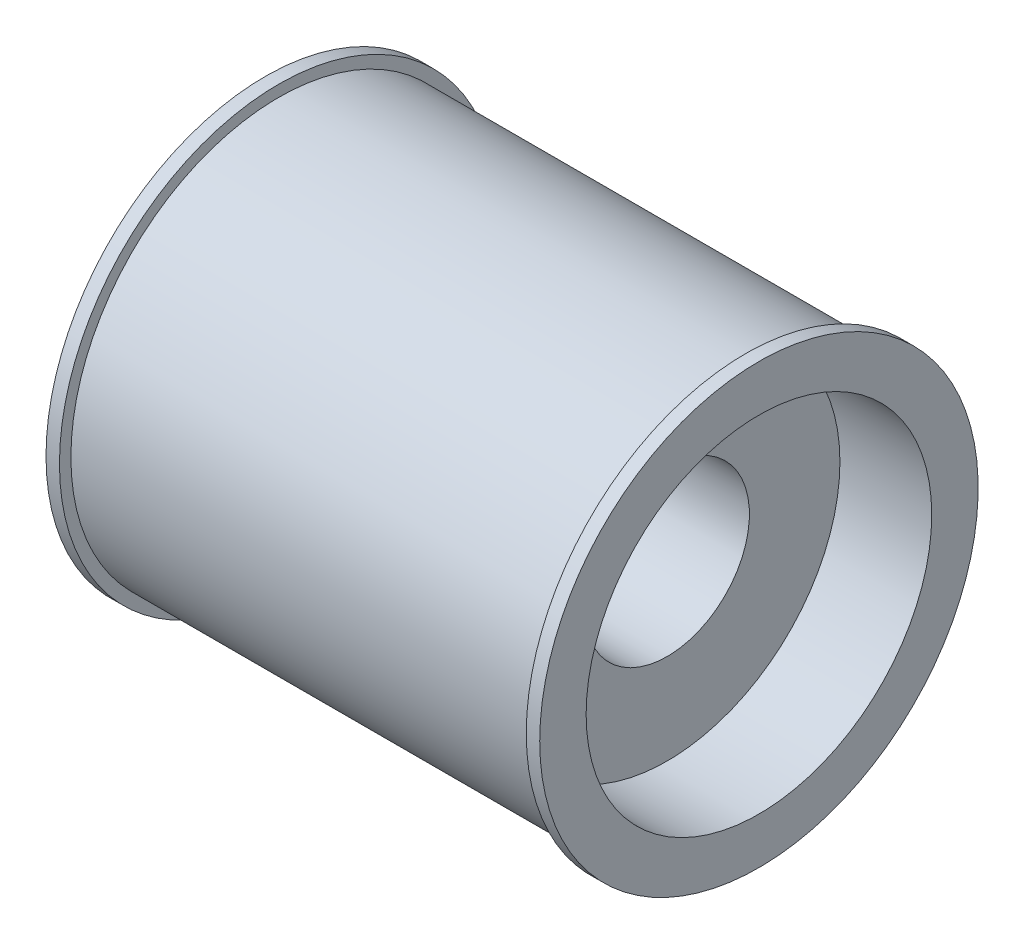
SolidWorks part; units mm, degrees
ref_plane "Front Plane" through (0, 0, 0) normal (0, 0, 1) x (1, 0, 0)
ref_plane "Top Plane" through (0, 0, 0) normal (0, 1, 0) x (1, 0, 0)
ref_plane "Right Plane" through (0, 0, 0) normal (1, 0, 0) x (0, 0, -1)
sketch "Sketch1" plane through (0, 0, 0) normal (0, 0, 1) x (1, 0, 0)
  line L0 (0, 0) -> (70.4282, 0) construction
  line L1 (0, 0) -> (0, 41.0522) construction
  line L10 (18.8432, 21) -> (30, 21)
  line L11 (-18.8432, 10) -> (18.8432, 10)
  line L12 (18.8432, 10) -> (18.8432, 21)
  line L14 (30, 21) -> (30, 26.6416)
  line L15 (30, 26.6416) -> (28.3651, 26.6416)
  line L16 (28.3651, 26.6416) -> (28.3651, 25.252)
  line L17 (28.3651, 25.252) -> (-28.3651, 25.252)
  line L19 (-28.3651, 26.6416) -> (-28.3651, 25.252)
  line L20 (-30, 26.6416) -> (-28.3651, 26.6416)
  line L21 (-30, 21) -> (-30, 26.6416)
  line L22 (-18.8432, 21) -> (-30, 21)
  line L23 (-18.8432, 10) -> (-18.8432, 21)
  dimension "D1" = 30
  dimension "D2" = 11
  dimension "D3" = 10
revolve "Revolve1" add sketch "Sketch1" angle 360 about L0
